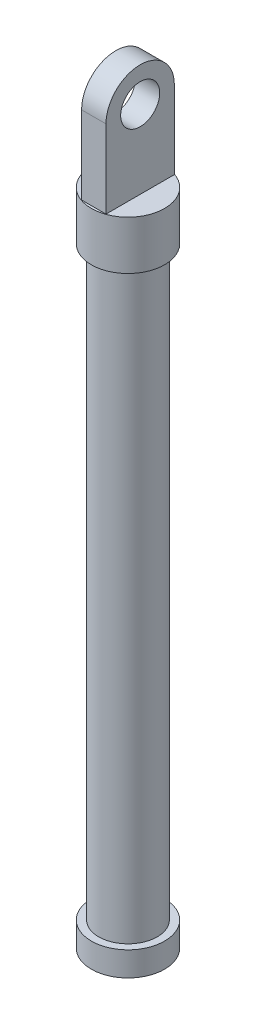
SolidWorks part; units mm, degrees
ref_plane "前基準面" through (0, 0, 0) normal (0, 0, 1) x (1, 0, 0)
ref_plane "上基準面" through (0, 0, 0) normal (0, 1, 0) x (1, 0, 0)
ref_plane "右基準面" through (0, 0, 0) normal (1, 0, 0) x (0, 0, -1)
sketch "草圖1" plane through (0, 0, 0) normal (0, 1, 0) x (1, 0, 0)
  circle A0 centre (0, 0) radius 7.5
  dimension "D1" = 15
extrude "填料-伸長1" add sketch "草圖1" along normal blind 5
sketch "草圖2" plane through (0, 5, 0) normal (0, 1, 0) x (1, 0, 0)
  circle A0 centre (0, 0) radius 6
  dimension "D1" = 12
extrude "填料-伸長2" add sketch "草圖2" along normal blind 130
sketch "草圖3" plane through (0, 0, 0) normal (1, 0, 0) x (0, 0, -1)
  line L0 (-7, 151) -> (-7, 135)
  line L1 (6, 135) -> (-6, 135) construction
  line L2 (7, 151) -> (7, 135)
  line L3 (7, 135) -> (-7, 135)
  arc A0 (7, 151) -> (-7, 151) centre (0, 151) ccw
  circle A2 centre (0, 151) radius 4
  dimension "D2" = 14
  dimension "D3" = 8
  dimension "D1" = 16
extrude "填料-伸長3" add sketch "草圖3" along normal mid plane 5
sketch "草圖4" plane through (0, 135, 0) normal (0, 1, 0) x (1, 0, 0)
  circle A0 centre (0, 0) radius 7.5
  dimension "D1" = 15
extrude "填料-伸長4" add sketch "草圖4" against normal blind 10
